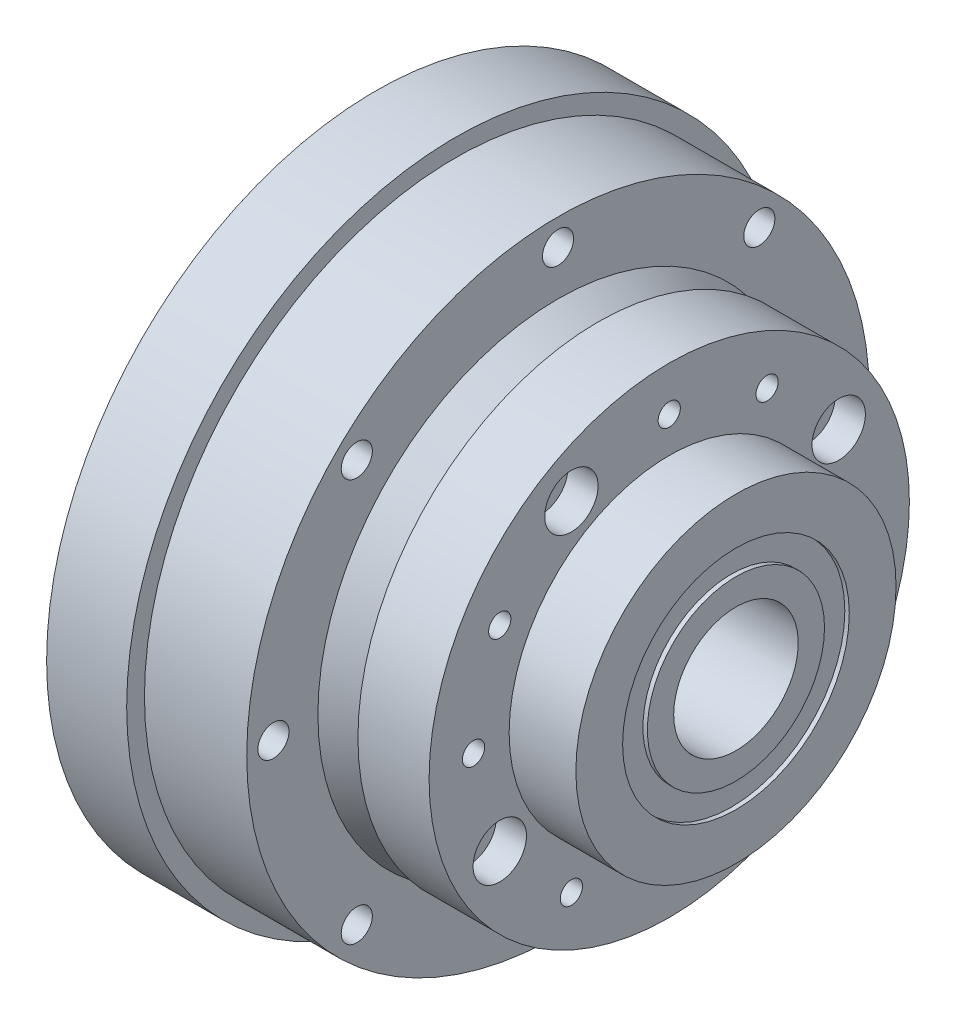
SolidWorks part; units mm, degrees
ref_plane "前视基准面" through (0, 0, 0) normal (0, 0, 1) x (1, 0, 0)
ref_plane "上视基准面" through (0, 0, 0) normal (0, 1, 0) x (1, 0, 0)
ref_plane "右视基准面" through (0, 0, 0) normal (1, 0, 0) x (0, 0, -1)
sketch "草图1" plane through (0, 0, 0) normal (0, 0, 1) x (1, 0, 0)
  line L0 (-65.2008, 0) -> (80.5899, 0) construction
  line L1 (0, 7) -> (0, 10)
  line L2 (0, 10) -> (12, 10)
  line L3 (12, 10) -> (12, 37)
  line L4 (12, 37) -> (21, 37)
  line L5 (21, 37) -> (21, 35)
  line L6 (21, 35) -> (32.5, 35)
  line L7 (32.5, 35) -> (32.5, 27)
  line L9 (37, 24.4019) -> (37, 27)
  line L10 (37, 27) -> (45, 27)
  line L11 (45, 27) -> (45, 18)
  line L12 (45, 18) -> (52.5, 18)
  line L13 (52.5, 18) -> (52.5, 7)
  line L14 (0, 7) -> (52.5, 7)
  line L15 (0, 0) -> (0, 43.251) construction
  line L17 (32.5, 27) -> (37, 24.4019)
  dimension "D1" = 74
  dimension "D2" = 20
  dimension "D3" = 14
  dimension "D4" = 70
  dimension "D5" = 54
  dimension "D6" = 36
  dimension "D7" = 12
  dimension "D8" = 9
  dimension "D9" = 20.5
  dimension "D10" = 52.5
  dimension "D11" = 8
  dimension "D12" = 7.5
  dimension "D13" = 60
revolve "旋转1" add sketch "草图1" angle 360 about L0
ref_axis "基准轴1" through (52.5, 0, 0) along (-1, 0, 0)
sketch "草图5" plane through (12, 0, 0) normal (-1, 0, 0) x (0, 0, 1)
  line L0 (0, 0) -> (0, 40.0957) construction
  circle A0 centre (0, 0) radius 32 construction
  circle A1 centre (0, 32) radius 1.75
  dimension "D1" = 64
  dimension "D2" = 3.5
extrude "切除-拉伸1" cut sketch "草图5" against normal up to next
pattern_circular "阵列(圆周)2" count 8 over 360 about axis through (0, 0, 0) along (1, 0, 0) of "切除-拉伸1"
hole_wizard "M3 螺纹孔2" positions "草图8" profile "草图7" tap size "M3" standard "GB"
sketch "草图8" plane through (45, 0, 0) normal (1, 0, 0) x (0, 0, -1)
  line L0 (0, 0) -> (0, 38.3972) construction
  circle A0 centre (0, 0) radius 22 construction
  point P0 (0, 22)
  dimension "D1" = 44
sketch "草图7" plane through (45, 22, 0) normal (0, 1, 0) x (0, 0, -1)
  line L0 (0, 0) -> (0, 12.2511)
  line L1 (0, 12.2511) -> (1.25, 11.5)
  line L2 (1.25, 11.5) -> (1.25, 0)
  line L5 (1.25, 0) -> (0, 0)
  line L10 (0, 12.2511) -> (-1.25, 11.5) construction
  line L11 (0, -6.35) -> (0, 107.95) construction
  dimension "螺纹孔钻头直径" = 2.5
  dimension "螺纹孔钻头深度" = 11.5
  dimension "导头角度" = 118
cosmetic thread "孔螺蚊线2" parameters "D1"=5, "D2"=3
pattern_circular "阵列(圆周)3" count 2 every 30 about axis through (52.5, 0, 0) along (-1, 0, 0) of "M3 螺纹孔2"
sketch "草图9" plane through (12, 0, 0) normal (-1, 0, 0) x (0, 0, 1)
  circle A0 centre (0, 0) radius 18
  circle A1 centre (0, 0) radius 10
  dimension "D1" = 36
extrude "凸台-拉伸1" add sketch "草图9" along normal blind 5.5 contours A1 | A0
ref_plane "基准面1" through (0, 10, 0) normal (0, 1, 0) x (1, 0, 0)
hole_wizard "M3 螺纹孔3" positions "草图11" profile "草图10" tap size "M3" standard "GB"
sketch "草图11" plane through (0, 10, 0) normal (0, 1, 0) x (1, 0, 0)
  line L0 (52.5, 0) -> (0, 0) construction
  line L1 (0, 10) -> (0, -10) construction
  point P0 (2.5, 0)
  dimension "D1" = 2.5
sketch "草图10" plane through (2.5, 10, 0) normal (1, 0, 0) x (0, 0, 1)
  line L0 (0, 0) -> (0, 7.2511)
  line L1 (0, 7.2511) -> (1.25, 6.5)
  line L2 (1.25, 6.5) -> (1.25, 0)
  line L5 (1.25, 0) -> (0, 0)
  line L10 (0, 7.2511) -> (-1.25, 6.5) construction
  line L11 (0, -6.35) -> (0, 107.95) construction
  dimension "螺纹孔钻头直径" = 2.5
  dimension "螺纹孔钻头深度" = 6.5
  dimension "导头角度" = 118
cosmetic thread "孔螺蚊线3" parameters "D1"=3.1125, "D2"=3
pattern_circular "阵列(圆周)4" count 3 over 360 about axis through (52.5, 0, 0) along (-1, 0, 0) of "M3 螺纹孔3"
sketch "草图12" plane through (52.5, 0, 0) normal (1, 0, 0) x (0, 0, -1)
  circle A0 centre (0, 0) radius 9.9587
  circle A1 centre (0, 0) radius 12.7426
extrude "切除-拉伸2" cut sketch "草图12" against normal blind 0.5 contours A1 | A0
sketch "草图13" plane through (6.5, 0, 0) normal (-1, 0, 0) x (0, 0, 1)
  circle A0 centre (0, 0) radius 10
  circle A1 centre (0, 0) radius 11.805
extrude "切除-拉伸3" cut sketch "草图13" against normal blind 0.5
pattern_circular "阵列(圆周)5" count 4 over 360 about axis through (0, 0, 0) along (1, 0, 0) of "阵列(圆周)3", "M3 螺纹孔2"
hole_wizard "打孔尺寸(%根据)内六角圆柱头螺钉的类型1" positions "草图15" profile "草图14" counterbore size "M3" standard "GB"
sketch "草图15" plane through (45, 0, 0) normal (1, 0, 0) x (0, 0, -1)
  line L2 (0, 0) -> (0, 39.1991) construction
  line L4 (0, 0) -> (36.1034, 20.8443) construction
  circle A0 centre (0, 0) radius 22 construction
  point P0 (19.0526, 11)
  dimension "D1" = 60
sketch "草图14" plane through (45, 11, -19.0526) normal (0, 1, 0) x (0, 0, -1)
  line L0 (0, 0) -> (0, 16.5215)
  line L1 (0, 16.5215) -> (1.7, 15.5)
  line L2 (1.7, 15.5) -> (1.7, 3.4)
  line L3 (1.7, 3.4) -> (3, 3.4)
  line L4 (3, 3.4) -> (3, 0)
  line L5 (3, 0) -> (0, 0)
  line L10 (0, 16.5215) -> (-1.7, 15.5) construction
  line L11 (0, -6.35) -> (0, 107.95) construction
  dimension "孔直径" = 3.4
  dimension "孔深度" = 15.5
  dimension "柱形沉头孔直径" = 6
  dimension "柱形沉头孔深度" = 3.4
  dimension "导头角度" = 118
pattern_circular "阵列(圆周)6" count 4 over 360 about axis through (0, 0, 0) along (1, 0, 0) of "打孔尺寸(%根据)内六角圆柱头螺钉的类型1"
